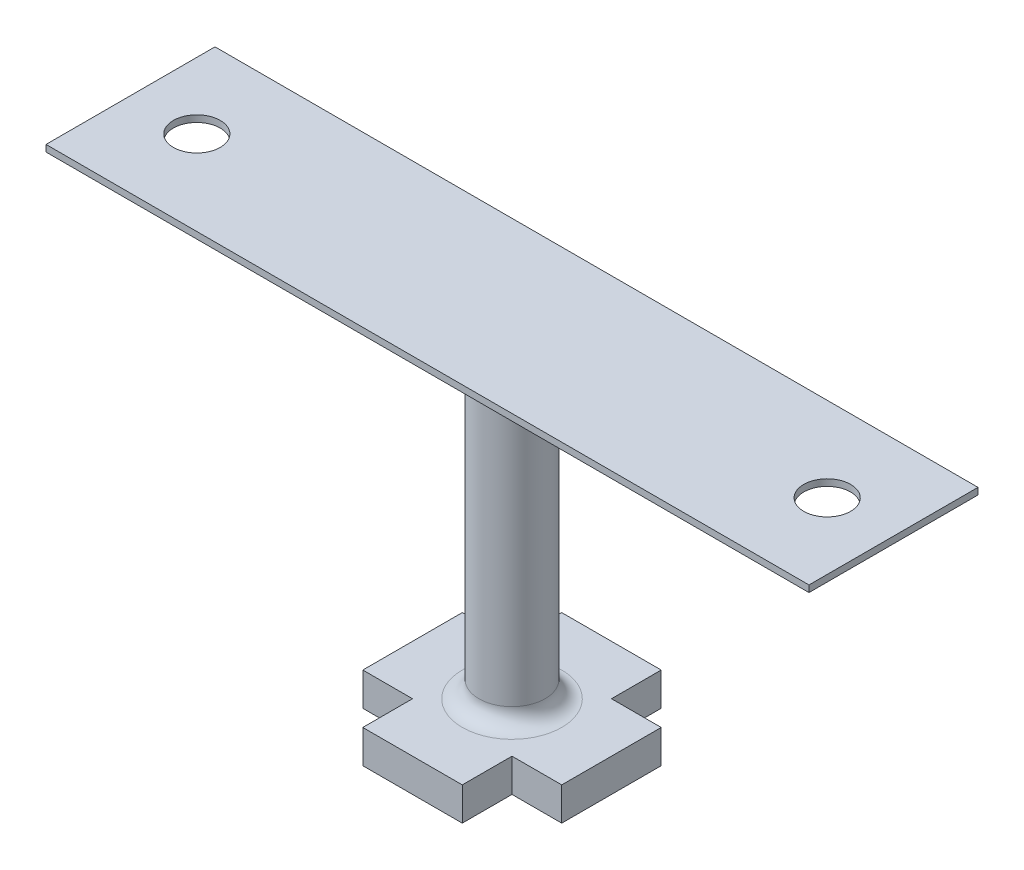
SolidWorks part; units mm, degrees
material "ASTM A36 Steel"
ref_plane "Front Plane" through (0, 0, 0) normal (0, 0, 1) x (1, 0, 0)
ref_plane "Top Plane" through (0, 0, 0) normal (0, 1, 0) x (1, 0, 0)
ref_plane "Right Plane" through (0, 0, 0) normal (1, 0, 0) x (0, 0, -1)
sketch "Sketch1" plane through (0, 0, 0) normal (0, 1, 0) x (1, 0, 0)
  line L5 (-113.4349, -17.0694) -> (113.4349, 17.0694) construction
  line L6 (-113.4349, 17.0694) -> (113.4349, -17.0694) construction
  line L11 (-113.4349, -17.0694) -> (113.4349, 17.0694) construction
  line L12 (-113.4349, 17.0694) -> (113.4349, -17.0694) construction
  line L13 (-115.06, -25.4875) -> (115.06, -25.4875)
  line L14 (-115.06, -25.4875) -> (-115.06, 25.4875)
  line L15 (-115.06, 25.4875) -> (115.06, 25.4875)
  line L16 (115.06, -25.4875) -> (115.06, 25.4875)
  line L17 (-115.06, -25.4875) -> (115.06, 25.4875) construction
  line L18 (-115.06, 25.4875) -> (115.06, -25.4875) construction
  circle A0 centre (-95.06, 0) radius 7.0582
  circle A1 centre (95.06, 0) radius 7.0582
  point P0 (0, 0)
  point P9 (0, 0)
  point P11 (0, 0)
  point P12 (0, 0)
  dimension "D1" = 190.12
  dimension "D2" = 20
  dimension "D3" = 20
extrude "Boss-Extrude1" add sketch "Sketch1" along normal blind 2
sketch "Sketch2" plane through (0, 2, 0) normal (0, 1, 0) x (1, 0, 0)
  circle A0 centre (0, 0) radius 10
extrude "Boss-Extrude2" add sketch "Sketch2" against normal blind 100
sketch "Sketch3" plane through (0, -98, 0) normal (0, -1, 0) x (-1, 0, 0)
  line L0 (15, 15) -> (30, 15)
  line L1 (-30, -15) -> (-15, -15)
  line L2 (-30, -15) -> (-30, 15)
  line L3 (-30, 15) -> (-15, 15)
  line L4 (30, -15) -> (30, 15)
  line L5 (-30, -15) -> (30, 15) construction
  line L6 (-30, 15) -> (30, -15) construction
  line L7 (-15, -30) -> (15, -30)
  line L8 (-15, -30) -> (-15, -15)
  line L9 (-15, 30) -> (15, 30)
  line L10 (15, -30) -> (15, -15)
  line L11 (-15, -30) -> (15, 30) construction
  line L12 (-15, 30) -> (15, -30) construction
  line L13 (-15, 15) -> (-15, 30)
  line L14 (15, 15) -> (15, 30)
  line L15 (15, -15) -> (30, -15)
  point P0 (0, 0)
  point P6 (0, 0)
extrude "Boss-Extrude3" add sketch "Sketch3" along normal blind 10
fillet "Fillet1" radius 5 2 edges at (0, -98, 10) (0, 0, -10)
